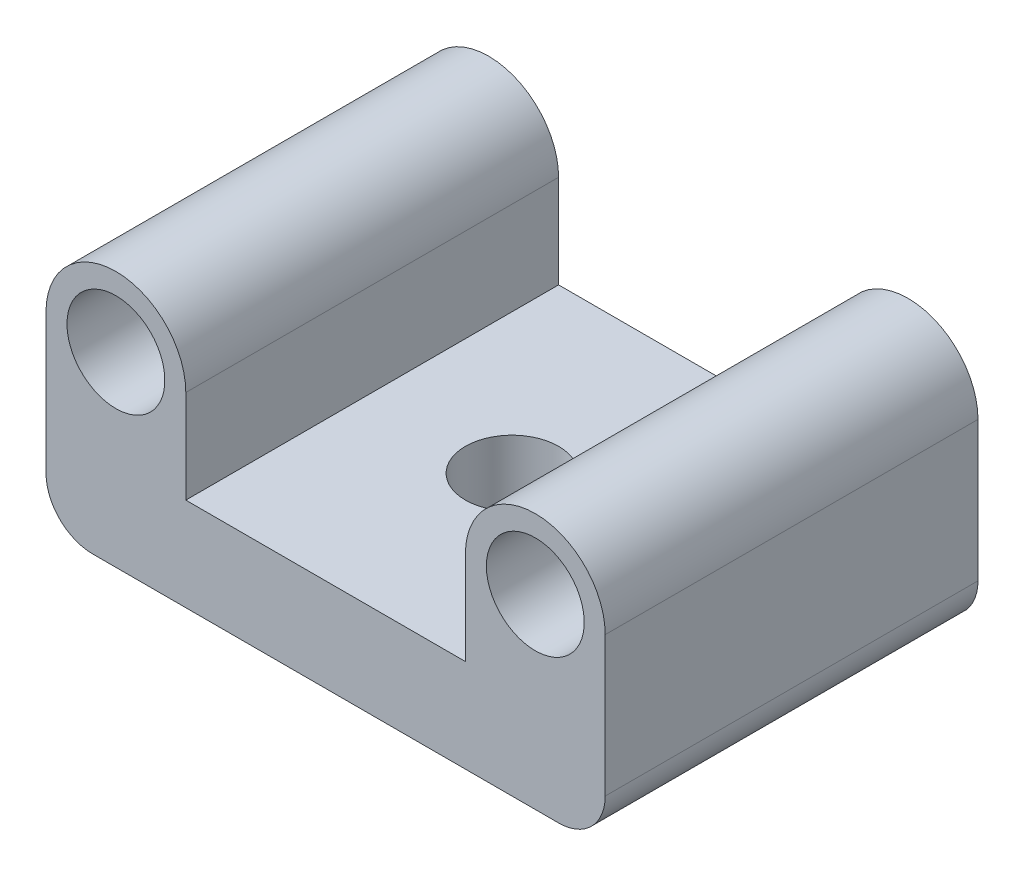
SolidWorks part; units mm, degrees
ref_plane "前视基准面" through (0, 0, 0) normal (0, 0, 1) x (1, 0, 0)
ref_plane "上视基准面" through (0, 0, 0) normal (0, 1, 0) x (1, 0, 0)
ref_plane "右视基准面" through (0, 0, 0) normal (1, 0, 0) x (0, 0, -1)
other "Configuration Table"
sketch "草图1" plane through (0, 0, 0) normal (0, 1, 0) x (1, 0, 0)
  line L0 (0, 0) -> (12, 0) construction
  line L1 (0, 4) -> (12, 4)
  line L2 (0, -4) -> (12, -4)
  line L3 (0, 4) -> (12, 4) construction
  line L4 (12, 4) -> (12, -4)
  line L5 (0, 4) -> (0, -4)
  dimension "D1" = 8
  dimension "D2" = 12
  dimension "D4" = 90
  dimension "D3" = 4
  dimension "D5" = 12
extrude "凸台-拉伸1" add sketch "草图1" along normal blind 2
sketch "草图10" plane through (0, 0, -4) normal (0, 0, -1) x (-1, 0, 0)
  line L0 (-12, 2) -> (-12, 4)
  line L2 (-9, 4) -> (-9, 2)
  line L3 (-12, 2) -> (0, 2) construction
  line L4 (-12, 2) -> (-9, 2)
  line L5 (-9, 2) -> (-3, 2) construction
  line L6 (-3, 2) -> (0, 2)
  line L7 (0, 2) -> (0, 4)
  line L9 (-3, 4) -> (-3, 2)
  arc A0 (-9, 4) -> (-12, 4) centre (-10.5, 4) ccw
  arc A1 (0, 4) -> (-3, 4) centre (-1.5, 4) ccw
  dimension "D3" = 6
  dimension "D7" = 1.5
  dimension "D8" = 1.5
  dimension "D1" = 2
  dimension "D2" = 3
  dimension "D4" = 3
  dimension "D5" = 2
  dimension "D6" = 3
  dimension "D9" = 4
extrude "凸台-拉伸6" add sketch "草图10" against normal up to surface (8 mm away) up to face at (6, 1, 4)
sketch "草图11" plane through (0, 0, -4) normal (0, 0, -1) x (-1, 0, 0)
  circle A2 centre (-1.5, 4) radius 1.05
  circle A3 centre (-10.5, 4) radius 1.05
  dimension "D2" = 2.1
  dimension "D3" = 2.1
extrude "切除-拉伸1" cut sketch "草图11" against normal through all
fillet "圆角3" radius 1 2 edges at (12, 0, 0) (0, 0, 0)
sketch "草图12" plane through (0, 0, 0) normal (0, -1, 0) x (1, 0, 0)
  line L0 (0, 0) -> (6, 0) construction
  circle A0 centre (6, 0) radius 1
  dimension "D2" = 2
  dimension "D1" = 6
extrude "切除-拉伸2" cut sketch "草图12" against normal up to surface (2 mm away) up to face at (6, 2, 0)
sketch "草图13" plane through (0, 0, 0) normal (0, -1, 0) x (1, 0, 0)
  circle A0 centre (6, 0) radius 1
  circle A1 centre (6, 0) radius 1.5
  dimension "D1" = 3
  dimension "D2" = 2
extrude "凸台-拉伸7" add sketch "草图13" along normal blind 1
